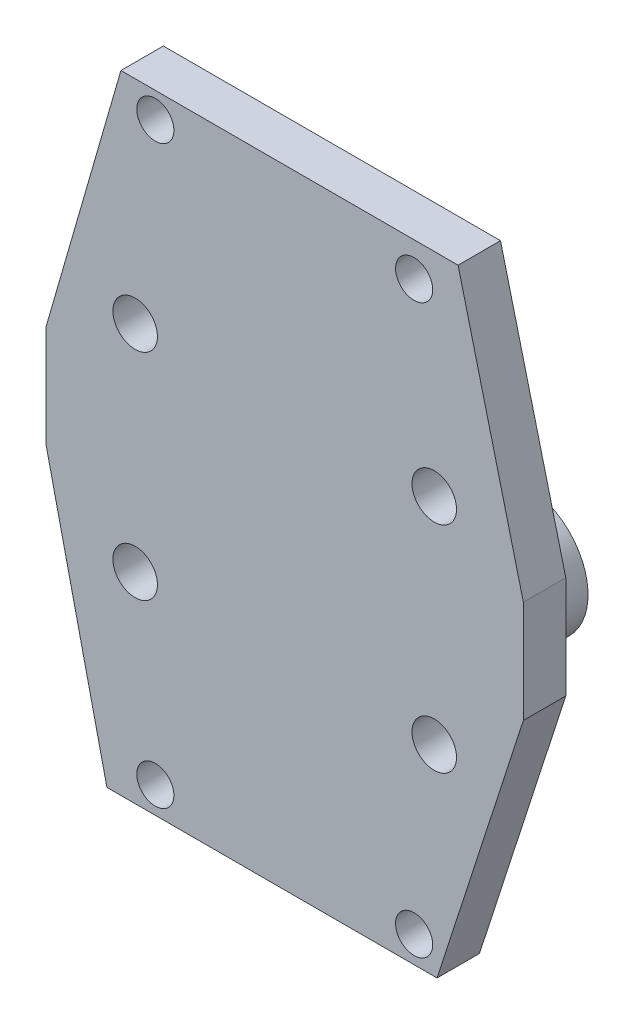
SolidWorks part; units mm, degrees
ref_plane "Alzado" through (0, 0, 0) normal (0, 0, 1) x (1, 0, 0)
ref_plane "Planta" through (0, 0, 0) normal (0, 1, 0) x (1, 0, 0)
ref_plane "Vista lateral" through (0, 0, 0) normal (1, 0, 0) x (0, 0, -1)
sketch "Croquis1" plane through (0, 0, 0) normal (0, 0, 1) x (1, 0, 0)
  line L1 (0, 0) -> (22, 0)
  line L2 (0, 0) -> (0, 55.2)
  line L3 (0, 55.2) -> (22, 55.2)
  line L4 (22, 0) -> (22, 55.2)
  dimension "D1" = 55.2
  dimension "D2" = 22
extrude "Saliente-Extruir1" add sketch "Croquis1" along normal blind 4
sketch "Croquis2" plane through (0, 55.2, 0) normal (0, 1, 0) x (1, 0, 0)
  line L0 (22, 0) -> (0, 0) construction
  line L1 (4.95, 0) -> (17.05, 0)
  line L2 (4.95, 0) -> (4.95, -4)
  line L3 (4.95, -4) -> (17.05, -4)
  line L4 (17.05, 0) -> (17.05, -4)
  line L5 (22, -4) -> (0, -4) construction
  line L6 (0, -4) -> (0, 0) construction
  dimension "D1" = 12.1
  dimension "D2" = 4.95
extrude "Cortar-Extruir1" cut sketch "Croquis2" against normal blind 9.6
sketch "Croquis3" plane through (0, 0, 0) normal (0, -1, 0) x (1, 0, 0)
  line L0 (0, 4) -> (22, 4) construction
  line L1 (4.95, 4) -> (17.05, 4)
  line L2 (4.95, 4) -> (4.95, 0)
  line L3 (4.95, 0) -> (17.05, 0)
  line L4 (17.05, 4) -> (17.05, 0)
  line L5 (0, 0) -> (22, 0) construction
  line L6 (0, 4) -> (0, 0) construction
  line L7 (22, 4) -> (22, 0) construction
  dimension "D1" = 4.95
  dimension "D2" = 4.95
extrude "Cortar-Extruir2" cut sketch "Croquis3" against normal blind 9.6
sketch "Croquis5" plane through (0, 9.6, 0) normal (0, -1, 0) x (1, 0, 0)
  line L0 (7.4, 4) -> (14.6, 4)
  line L1 (17.05, 4) -> (4.95, 4) construction
  line L2 (4.95, -1.5) -> (17.05, -1.5)
  arc A2 (7.4, 4) -> (4.95, -1.5) centre (12.4499, -1.5452) ccw
  arc A3 (17.05, -1.5) -> (14.6, 4) centre (9.5501, -1.5452) ccw
  dimension "D1" = 7.2
  dimension "D2" = 2.45
extrude "Cortar-Extruir3" cut sketch "Croquis5" against normal blind 16
sketch "Croquis7" plane through (0, 45.6, 0) normal (0, 1, 0) x (1, 0, 0)
  line L5 (4.95, -4) -> (17.05, -4) construction
  line L11 (4.95, 1.5) -> (17.05, 1.5)
  line L12 (7.4, -4) -> (14.6, -4)
  arc A3 (4.95, 1.5) -> (7.4, -4) centre (12.4499, 1.5452) ccw
  arc A4 (14.6, -4) -> (17.05, 1.5) centre (9.5501, 1.5452) ccw
extrude "Cortar-Extruir4" cut sketch "Croquis7" against normal blind 16
sketch "Croquis9" plane through (0, 0, 0) normal (0, 0, -1) x (-1, 0, 0)
  line L1 (-16.8892, 29.6) -> (-5.1108, 29.6)
  line L2 (-16.8892, 29.6) -> (-16.8892, 25.6)
  line L3 (-16.8892, 25.6) -> (-5.1108, 25.6)
  line L4 (-5.1108, 29.6) -> (-5.1108, 25.6)
extrude "Cortar-Extruir5" cut sketch "Croquis9" against normal blind 2
sketch "Croquis11" plane through (0, 55.2, 0) normal (0, 1, 0) x (1, 0, 0)
  line L0 (0, -4) -> (4.95, -4) construction
  line L1 (4.95, -4) -> (4.95, 0) construction
  line L2 (4.95, 0) -> (0, 0) construction
  line L3 (0, 0) -> (0, -4) construction
  line L4 (22, 0) -> (17.05, 0) construction
  line L5 (17.05, 0) -> (17.05, -4) construction
  line L6 (17.05, -4) -> (22, -4) construction
  line L7 (22, -4) -> (22, 0) construction
  line L8 (0, -4) -> (4.95, -4)
  line L9 (4.95, -4) -> (4.95, 0)
  line L10 (4.95, 0) -> (0, 0)
  line L11 (0, 0) -> (0, -4)
  line L12 (22, 0) -> (17.05, 0)
  line L13 (17.05, 0) -> (17.05, -4)
  line L14 (17.05, -4) -> (22, -4)
  line L15 (22, -4) -> (22, 0)
extrude "Saliente-Extruir3" add sketch "Croquis11" along normal blind 2
sketch "Croquis12" plane through (4.95, 0, 0) normal (1, 0, 0) x (0, 0, -1)
  line L0 (-4, 57.2) -> (0, 57.2)
  line L1 (0, 57.2) -> (0, 55.4)
  line L2 (0, 45.6) -> (0, 57.2) construction
  line L3 (0, 55.4) -> (-4, 55.4)
  line L4 (-4, 45.6) -> (-4, 57.2) construction
  line L5 (-4, 55.4) -> (-4, 57.2)
extrude "Saliente-Extruir4" add sketch "Croquis12" along normal blind 12.1
sketch "Croquis13" plane through (0, 0, 0) normal (0, -1, 0) x (1, 0, 0)
  line L0 (22, 4) -> (17.05, 4) construction
  line L1 (17.05, 4) -> (17.05, 0) construction
  line L2 (17.05, 0) -> (22, 0) construction
  line L3 (22, 0) -> (22, 4) construction
  line L4 (0, 0) -> (4.95, 0) construction
  line L5 (4.95, 0) -> (4.95, 4) construction
  line L6 (4.95, 4) -> (0, 4) construction
  line L7 (0, 4) -> (0, 0) construction
  line L8 (22, 4) -> (17.05, 4)
  line L9 (17.05, 4) -> (17.05, 0)
  line L10 (17.05, 0) -> (22, 0)
  line L11 (22, 0) -> (22, 4)
  line L12 (0, 0) -> (4.95, 0)
  line L13 (4.95, 0) -> (4.95, 4)
  line L14 (4.95, 4) -> (0, 4)
  line L15 (0, 4) -> (0, 0)
extrude "Saliente-Extruir5" add sketch "Croquis13" along normal blind 2
sketch "Croquis14" plane through (4.95, 0, 0) normal (1, 0, 0) x (0, 0, -1)
  line L0 (-4, 9.6) -> (-4, -2) construction
  line L1 (0, -2) -> (-4, -2)
  line L2 (0, -2) -> (0, -0.2)
  line L3 (0, -0.2) -> (-4, -0.2)
  line L4 (-4, -2) -> (-4, -0.2)
extrude "Saliente-Extruir6" add sketch "Croquis14" along normal blind 12.1
sketch "Croquis17" plane through (0, 0, 0) normal (-1, 0, 0) x (0, 0, 1)
  line L4 (0, 57.2) -> (0, -2)
  line L5 (0, -2) -> (4, -2)
  line L6 (4, -2) -> (4, 57.2)
  line L7 (4, 57.2) -> (0, 57.2)
  line L8 (0, 57.2) -> (0, -2)
  line L9 (0, -2) -> (4, -2)
  line L10 (4, -2) -> (4, 57.2)
  line L13 (4, 57.2) -> (0, 57.2)
  dimension "D1" = 0
extrude "Saliente-Extruir8" add sketch "Croquis17" along normal blind 11.5 contours L8 L9 L10 L13
sketch "Croquis18" plane through (22, 0, 0) normal (1, 0, 0) x (0, 0, -1)
  line L4 (0, -2) -> (0, 57.2)
  line L5 (0, 57.2) -> (-4, 57.2)
  line L6 (-4, 57.2) -> (-4, -2)
  line L7 (-4, -2) -> (0, -2)
  line L8 (0, -2) -> (0, 57.2)
  line L10 (-4, 57.2) -> (-4, -2)
  line L11 (-4, -2) -> (0, -2)
  line L13 (0, 57.2) -> (-4, 57.2)
  dimension "D1" = 0
extrude "Saliente-Extruir9" add sketch "Croquis18" along normal blind 11.5
sketch "Croquis19" plane through (0, 0, 0) normal (0, 0, -1) x (-1, 0, 0)
  line L0 (11.5, -2) -> (-33.5, -2) construction
  line L3 (11.5, 57.2) -> (11.5, -2) construction
  circle A0 centre (-23.2, 54) radius 1.75
  circle A1 centre (1.2, 54.8) radius 1.75
  circle A2 centre (1.2, 0.5) radius 1.75
  circle A3 centre (-23.2, 0.5) radius 1.75
  dimension "D1" = 3.5
  dimension "D2" = 3.5
  dimension "D3" = 3.5
  dimension "D4" = 3.5
  dimension "D5" = 2.5
  dimension "D6" = 2.5
  dimension "D7" = 53.5
  dimension "D8" = 54.3
  dimension "D9" = 10.3
  dimension "D10" = 24.4
  dimension "D11" = 24.4
  dimension "D12" = 10.3
extrude "Cortar-Extruir6" cut sketch "Croquis19" against normal blind 11.5
sketch "Croquis21" plane through (0, 0, 0) normal (0, 0, -1) x (-1, 0, 0)
  line L0 (-33.5, 27.6) -> (11.5, 27.6) construction
  line L18 (-33.5, -2) -> (-33.5, 57.2) construction
  line L19 (11.5, 57.2) -> (11.5, -2) construction
  line L20 (-27.3455, 57.2) -> (-33.5, 32.7559)
  line L21 (-33.5, 57.2) -> (11.5, 57.2) construction
  line L22 (-33.5, 32.7559) -> (-33.5, 57.2)
  line L23 (-33.5, 57.2) -> (-27.3455, 57.2)
  line L24 (4.4457, 57.2) -> (11.5, 32.7559)
  line L25 (11.5, 32.7559) -> (11.5, 57.2)
  line L26 (11.5, 57.2) -> (4.4457, 57.2)
  line L27 (-25.3637, -2) -> (-33.5, 23.0947)
  line L28 (11.5, -2) -> (-33.5, -2) construction
  line L29 (-33.5, 23.0947) -> (-33.5, -2)
  line L30 (-33.5, -2) -> (-25.3637, -2)
  line L31 (11.5, 23.0947) -> (5.7669, -2)
  line L32 (5.7669, -2) -> (11.5, -2)
  line L33 (11.5, -2) -> (11.5, 23.0947)
extrude "Cortar-Extruir7" cut sketch "Croquis21" against normal blind 10
ref_plane "Plano1" through (0, 0, -7.5) normal (0, 0, -1) x (-1, 0, 0)
ref_plane "Plano2" through (0, 0, -7.5) normal (0, 0, -1) x (-1, 0, 0)
sketch "Croquis27" plane through (0, 0, 0) normal (0, 0, -1) x (-1, 0, 0)
  line L1 (-17.05, 55.4) -> (-4.95, 55.4)
  line L2 (-17.05, 55.4) -> (-17.05, -0.2)
  line L3 (-17.05, -0.2) -> (-4.95, -0.2)
  line L4 (-4.95, 55.4) -> (-4.95, -0.2)
extrude "Cortar-Extruir8" cut sketch "Croquis27" against normal blind 10
sketch "Croquis28" plane through (0, 55.4, 0) normal (0, -1, 0) x (1, 0, 0)
  line L4 (4.95, 4) -> (4.95, 0)
  line L5 (4.95, 0) -> (17.05, 0)
  line L6 (17.05, 0) -> (17.05, 4)
  line L7 (17.05, 4) -> (4.95, 4)
  line L8 (4.95, 4) -> (4.95, 0)
  line L9 (4.95, 0) -> (17.05, 0)
  line L10 (17.05, 0) -> (17.05, 4)
  line L11 (17.05, 4) -> (4.95, 4)
  dimension "D1" = 0
extrude "Saliente-Extruir10" add sketch "Croquis28" along normal blind 55.6
sketch "Croquis29" plane through (0, 0, 0) normal (0, 0, -1) x (-1, 0, 0)
  line L0 (-21.25, 32.5272) -> (-21.25, 23.3234)
  line L2 (-1.113, 23.6532) -> (-1.113, 32.1974)
  arc A0 (-21.25, 32.5272) -> (-21.25, 23.3234) centre (-25.1, 27.9253) ccw
  arc A1 (-1.113, 23.6532) -> (-1.113, 32.1974) centre (3.1, 27.9253) ccw
extrude "Saliente-Extruir11" add sketch "Croquis29" along normal blind 4.5
sketch "Croquis25" plane through (0, 0, -7.5) normal (0, 0, -1) x (-1, 0, 0)
  line L0 (-33.5, 27.9253) -> (-25.1, 27.9253) construction
  line L1 (-33.5, 23.0947) -> (-33.5, 32.7559) construction
  line L2 (11.5, 32.7559) -> (11.5, 23.0947) construction
  line L3 (-25.1, 22.9253) -> (-25.1, 32.9253)
  line L5 (-20.1, 27.9253) -> (-1.9, 27.9253) construction
  line L6 (8.1, 27.9253) -> (11.5, 27.9253) construction
  arc A0 (-25.1, 32.9253) -> (-25.1, 22.9253) centre (-25.1, 27.9253) ccw
  dimension "D1" = 10
  dimension "D3" = 8.4
revolve "Cortar-Revolución3" cut sketch "Croquis25" angle 360 about L3
sketch "Croquis26" plane through (0, 0, -7.5) normal (0, 0, -1) x (-1, 0, 0)
  line L0 (11.5, 27.9253) -> (3.1, 27.9253) construction
  line L1 (11.5, 32.7559) -> (11.5, 23.0947) construction
  line L2 (3.1, 32.9253) -> (3.1, 22.9253)
  arc A0 (3.1, 22.9253) -> (3.1, 32.9253) centre (3.1, 27.9253) ccw
  dimension "D1" = 8.4
revolve "Cortar-Revolución4" cut sketch "Croquis26" angle 360 about L2
sketch "Croquis30" plane through (0, 0, 0) normal (0, 0, -1) x (-1, 0, 0)
  circle A0 centre (-25.1, 37.1948) radius 2.1
  circle A1 centre (-25.1, 16.9253) radius 2.1
  circle A2 centre (3.1, 37.1948) radius 2.1
  circle A3 centre (3.1, 16.9253) radius 2.1
extrude "Cortar-Extruir9" cut sketch "Croquis30" against normal blind 10
